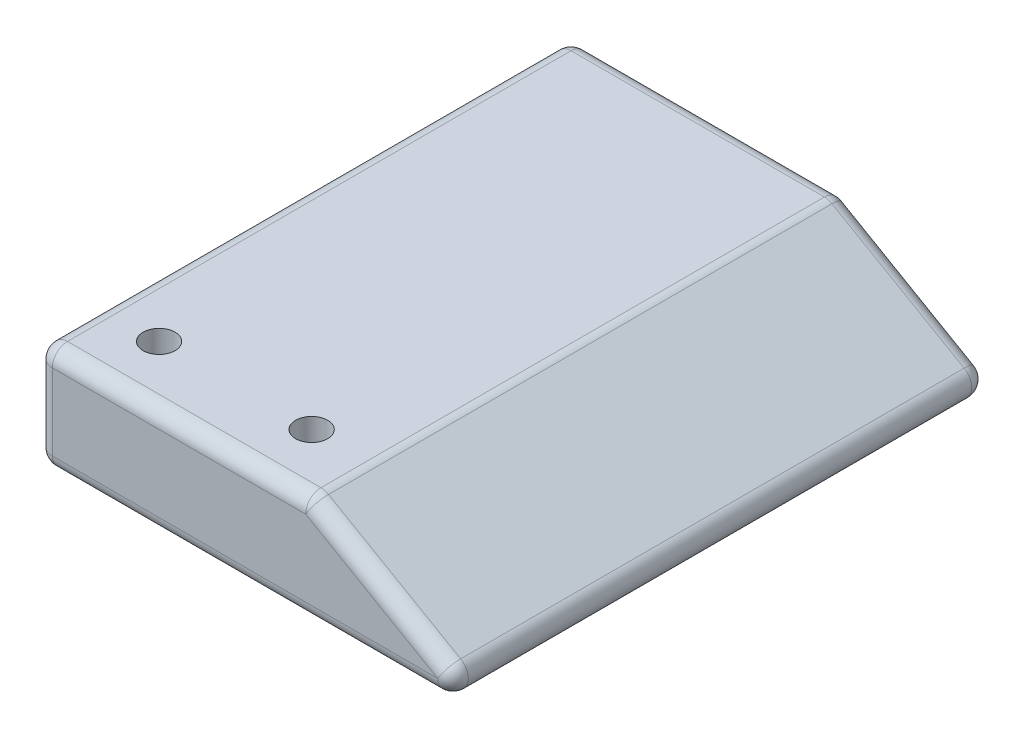
SolidWorks part; units mm, degrees
ref_plane "Front Plane" through (0, 0, 0) normal (0, 0, 1) x (1, 0, 0)
ref_plane "Top Plane" through (0, 0, 0) normal (0, 1, 0) x (1, 0, 0)
ref_plane "Right Plane" through (0, 0, 0) normal (1, 0, 0) x (0, 0, -1)
sketch "Sketch1" plane through (0, 0, 0) normal (0, 0, 1) x (1, 0, 0)
  line L0 (0, 0) -> (0, 14)
  line L1 (0, 14) -> (35.7513, 14)
  line L2 (35.7513, 14) -> (60, 0)
  line L3 (60, 0) -> (0, 0)
  dimension "D1" = 60
  dimension "D2" = 30
  dimension "D3" = 14
extrude "Boss-Extrude1" add sketch "Sketch1" along normal blind 70
fillet "Fillet1" radius 2 12 edges at (60, 0, 35) (35.7513, 14, 35) (47.8756, 7, 0) (17.8756, 14, 0) (30, 0, 0) (17.8756, 14, 70) (47.8756, 7, 70) (30, 0, 70) (0, 14, 35) (0, 7, 70) (0, 0, 35) (0, 7, 0)
hole_wizard "M5 Tapped Hole1" positions "Sketch2" profile "Sketch3" tap size "M5" standard "ISO"
sketch "Sketch2" plane through (0, 14, 0) normal (0, 1, 0) x (1, 0, 0)
  line L0 (0, -68) -> (0, -2) construction
  line L2 (35.2154, -70) -> (2, -70) construction
  point P0 (8, -62)
  point P2 (28, -62)
  point P9 (0, 0)
  dimension "D1" = 8
  dimension "D2" = 20
  dimension "D3" = 8
cosmetic thread "Hole Thread1" parameters "D1"=10, "D2"=5
cosmetic thread "Hole Thread2" parameters "D1"=10, "D2"=5
sketch "Sketch3" plane through (8, 14, 62) normal (1, 0, 0) x (0, 0, 1)
  line L0 (0, 0) -> (0, 13.7618)
  line L1 (0, 13.7618) -> (2.1, 12.5)
  line L2 (2.1, 12.5) -> (2.1, 0)
  line L5 (2.1, 0) -> (0, 0)
  line L10 (0, 13.7618) -> (-2.1, 12.5) construction
  line L11 (0, -6.35) -> (0, 107.95) construction
  dimension "Tap Drill Dia." = 4.2
  dimension "Tap Drill Depth" = 12.5
  dimension "Drill Angle" = 118
